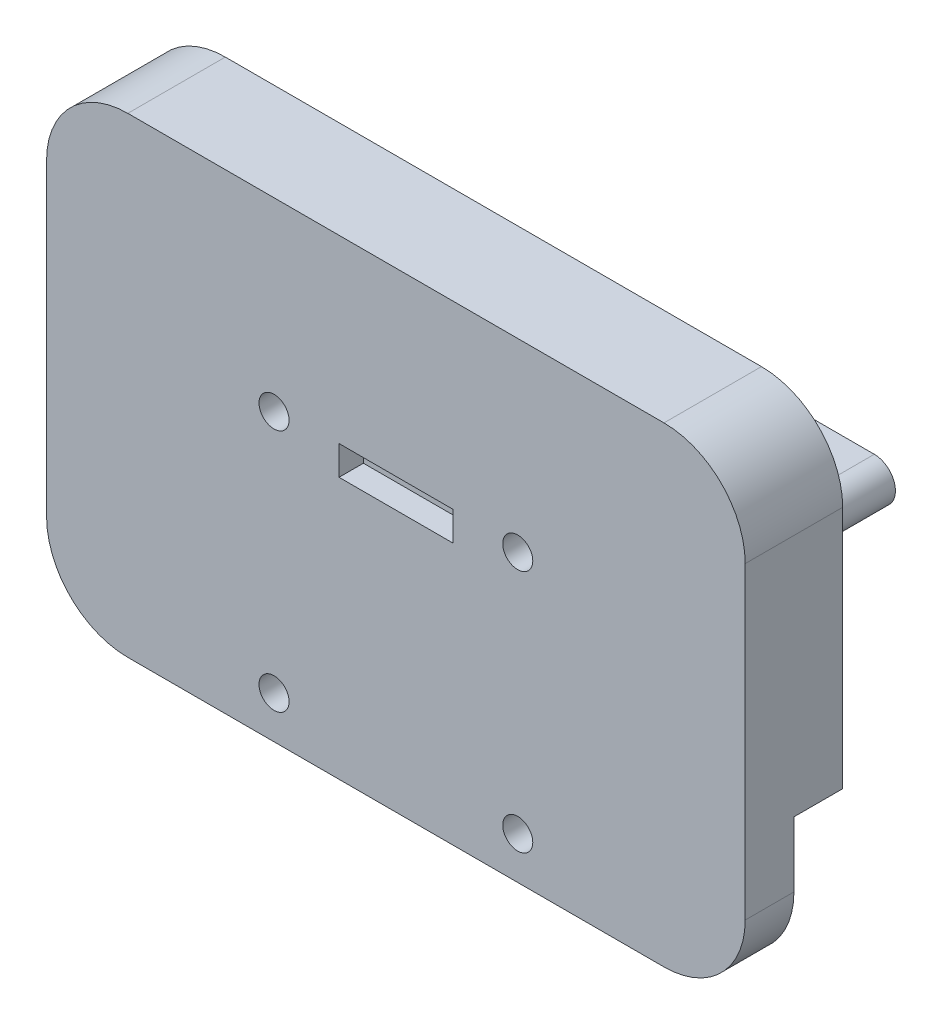
SolidWorks part; units mm, degrees
ref_plane "前视基准面" through (0, 0, 0) normal (0, 0, 1) x (1, 0, 0)
ref_plane "上视基准面" through (0, 0, 0) normal (0, 1, 0) x (1, 0, 0)
ref_plane "右视基准面" through (0, 0, 0) normal (1, 0, 0) x (0, 0, -1)
sketch "草图1" plane through (0, 0, 0) normal (0, 0, 1) x (1, 0, 0)
  line L1 (-13.5, 10) -> (13.5, 10)
  line L2 (-13.5, 10) -> (-13.5, -10)
  line L3 (-13.5, -10) -> (13.5, -10)
  line L4 (13.5, 10) -> (13.5, -10)
  line L5 (-13.5, 10) -> (13.5, -10) construction
  line L6 (-13.5, -10) -> (13.5, 10) construction
  point P0 (0, 0)
extrude "凸台-拉伸1" add sketch "草图1" along normal blind 4
ref_plane "基准面1" through (0, 0, 0) normal (-1, 0, 0) x (0, 0, 1)
extrude "切除-拉伸1" cut sketch "草图2" against normal blind 1.5
sketch "草图2" plane through (6.4149, -0.5973, 4) normal (0, 0, 1) x (1, 0, 0)
  line L8 (-9.8149, 8.3973) -> (-9.8149, 6.7973)
  line L9 (-3.0149, 8.3973) -> (-9.8149, 8.3973)
  line L10 (-3.0149, 6.7973) -> (-3.0149, 8.3973)
  line L11 (-9.8149, 6.7973) -> (-3.0149, 6.7973)
sketch "草图4" plane through (0, 0, 0) normal (0, 0, -1) x (-1, 0, 0)
  line L0 (-13.5, 10) -> (-13.5, 14)
  line L1 (-13.5, 14) -> (13.5, 14)
  line L2 (13.5, 14) -> (13.5, 10)
  line L4 (-13.5, 10) -> (-13.5, -10)
  line L5 (-13.5, -10) -> (13.5, -10)
  line L6 (13.5, -10) -> (13.5, 10)
  line L7 (13.5, 10) -> (-13.5, 10)
  line L8 (-13.5, 10) -> (-13.5, -6)
  line L10 (13.5, -6) -> (13.5, 10)
  line L12 (-13.5, -6) -> (13.5, -6)
  dimension "D1" = 0
extrude "凸台-拉伸2" add sketch "草图4" along normal blind 3
sketch "草图5" plane through (0, 10, 0) normal (0, 1, 0) x (1, 0, 0)
  line L4 (13.5, 0) -> (-13.5, 0)
  line L5 (-13.5, 0) -> (-13.5, -4)
  line L6 (-13.5, -4) -> (13.5, -4)
  line L7 (13.5, -4) -> (13.5, 0)
  line L8 (13.5, 0) -> (-13.5, 0)
  line L9 (-13.5, 0) -> (-13.5, -4)
  line L10 (-13.5, -4) -> (13.5, -4)
  line L11 (13.5, -4) -> (13.5, 0)
  dimension "D1" = 0
extrude "凸台-拉伸3" add sketch "草图5" along normal up to surface (4 mm away) up to face at (0, 14, -1.5)
sketch "草图9" plane through (0, 0, -3) normal (0, 0, -1) x (-1, 0, 0)
  line L4 (-13.5, 14) -> (-13.5, -6)
  line L5 (-13.5, -6) -> (13.5, -6)
  line L6 (13.5, -6) -> (13.5, 14)
  line L7 (13.5, 14) -> (-13.5, 14)
  line L8 (-13.5, 14) -> (-13.5, -6)
  line L9 (-13.5, -6) -> (13.5, -6)
  line L10 (13.5, -6) -> (13.5, 14)
  line L11 (13.5, 14) -> (-13.5, 14)
  dimension "D1" = 0
extrude "切除-拉伸4" cut sketch "草图9" against normal blind 2
sketch "草图10" plane through (-13.5, 0, 0) normal (-1, 0, 0) x (0, 0, 1)
  line L6 (-1, 14) -> (-1, -6)
  line L7 (-1, -6) -> (0, -6)
  line L8 (0, -6) -> (0, -10)
  line L9 (0, -10) -> (4, -10)
  line L10 (4, -10) -> (4, 14)
  line L11 (4, 14) -> (-1, 14)
  line L12 (-1, 14) -> (-1, -6)
  line L13 (-1, -6) -> (0, -6)
  line L14 (0, -6) -> (0, -10)
  line L15 (0, -10) -> (4, -10)
  line L16 (4, -10) -> (4, 14)
  line L17 (4, 14) -> (-1, 14)
  dimension "D1" = 0
extrude "凸台-拉伸6" add sketch "草图10" along normal blind 8
sketch "草图11" plane through (13.5, 0, 0) normal (1, 0, 0) x (0, 0, -1)
  line L6 (1, -6) -> (1, 14)
  line L7 (1, 14) -> (-4, 14)
  line L8 (-4, 14) -> (-4, -10)
  line L9 (-4, -10) -> (0, -10)
  line L10 (0, -10) -> (0, -6)
  line L11 (0, -6) -> (1, -6)
  line L12 (1, -6) -> (1, 14)
  line L13 (1, 14) -> (-4, 14)
  line L14 (-4, 14) -> (-4, -10)
  line L15 (-4, -10) -> (0, -10)
  line L16 (0, -10) -> (0, -6)
  line L17 (0, -6) -> (1, -6)
  dimension "D1" = 0
extrude "凸台-拉伸7" add sketch "草图11" along normal blind 8
sketch "草图12" plane through (0, 0, -1) normal (0, 0, -1) x (-1, 0, 0)
  line L1 (-21.5, -2) -> (21.5, -2)
  line L4 (21.5, 14) -> (-21.5, 14)
  line L5 (-21.5, 14) -> (-21.5, -6)
  line L6 (-21.5, -6) -> (21.5, -6)
  line L7 (21.5, -6) -> (21.5, 14)
  line L8 (21.5, 14) -> (-21.5, 14)
  line L9 (-21.5, 14) -> (-21.5, -2)
  line L11 (21.5, -2) -> (21.5, 14)
  dimension "D1" = 0
extrude "凸台-拉伸8" add sketch "草图12" along normal blind 20
extrude "切除-拉伸5" cut sketch "草图13" against normal blind 20
sketch "草图13" plane through (6.4149, -0.5973, -21) normal (0, 0, -1) x (-1, 0, 0)
  line L1 (26.2832, 7.1911) -> (21.0492, 4.7486)
  line L4 (27.9149, -1.4027) -> (27.9149, 14.5973)
  line L9 (18.9149, 6.1078) -> (18.9149, 8.0973)
  line L11 (19.9149, 9.0973) -> (25.8603, 9.0973)
  line L12 (-13.4534, 7.1911) -> (-8.2194, 4.7486)
  line L13 (-6.0851, 6.1078) -> (-6.0851, 8.0973)
  line L14 (-7.0851, 9.0973) -> (-13.0305, 9.0973)
  line L16 (27.9149, 14.5973) -> (-15.0851, 14.5973)
  line L18 (-15.0851, 14.5973) -> (-15.0851, -1.4027)
  line L20 (-15.0851, -1.4027) -> (27.9149, -1.4027)
  arc A1 (18.9149, 6.1078) -> (21.0492, 4.7486) centre (20.4149, 6.1078) ccw
  arc A3 (19.9149, 9.0973) -> (18.9149, 8.0973) centre (19.9149, 8.0973) ccw
  arc A5 (26.2832, 7.1911) -> (25.8603, 9.0973) centre (25.8603, 8.0973) ccw
  arc A12 (-8.2194, 4.7486) -> (-6.0851, 6.1078) centre (-7.5851, 6.1078) ccw
  arc A13 (-6.0851, 8.0973) -> (-7.0851, 9.0973) centre (-7.0851, 8.0973) ccw
  arc A14 (-13.0305, 9.0973) -> (-13.4534, 7.1911) centre (-13.0305, 8.0973) ccw
extrude "切除-拉伸6" cut sketch "草图14" against normal blind 16
sketch "草图14" plane through (6.4149, -0.5973, -21) normal (0, 0, -1) x (-1, 0, 0)
  line L6 (21.0492, 4.7486) -> (26.2832, 7.1911)
  line L7 (25.8603, 9.0973) -> (19.9149, 9.0973)
  line L8 (18.9149, 8.0973) -> (18.9149, 6.1078)
  line L12 (-7.0851, 9.0973) -> (-13.0305, 9.0973)
  line L13 (-13.4534, 7.1911) -> (-8.2194, 4.7486)
  line L14 (-6.0851, 6.1078) -> (-6.0851, 8.0973)
  arc A6 (26.2832, 7.1911) -> (25.8603, 9.0973) centre (25.8603, 8.0973) ccw
  arc A7 (19.9149, 9.0973) -> (18.9149, 8.0973) centre (19.9149, 8.0973) ccw
  arc A8 (18.9149, 6.1078) -> (21.0492, 4.7486) centre (20.4149, 6.1078) ccw
  arc A12 (-13.0305, 9.0973) -> (-13.4534, 7.1911) centre (-13.0305, 8.0973) ccw
  arc A13 (-8.2194, 4.7486) -> (-6.0851, 6.1078) centre (-7.5851, 6.1078) ccw
  arc A14 (-6.0851, 8.0973) -> (-7.0851, 9.0973) centre (-7.0851, 8.0973) ccw
sketch "草图15" plane through (0, 0, 4) normal (0, 0, 1) x (1, 0, 0)
  line L0 (-12.2968, 9.9409) -> (-18.5405, 6.1947)
  line L1 (-18.5405, 6.1947) -> (-18.9078, 5.4396)
  line L2 (-18.9078, 5.4396) -> (-12.2968, 9.4062)
  line L3 (-12.2968, 9.4062) -> (-12.2968, 9.9409)
  line L4 (-12.2968, 4.4409) -> (-18.5405, 0.6947)
  line L5 (-12.2968, 3.9062) -> (-12.2968, 4.4409)
  line L6 (-18.9078, -0.0604) -> (-12.2968, 3.9062)
  line L7 (-18.5405, 0.6947) -> (-18.9078, -0.0604)
  line L8 (-12.2968, -1.0591) -> (-18.5405, -4.8053)
  line L9 (-12.2968, -1.5938) -> (-12.2968, -1.0591)
  line L10 (-18.9078, -5.5604) -> (-12.2968, -1.5938)
  line L11 (-18.5405, -4.8053) -> (-18.9078, -5.5604)
  dimension "D1" = 3
sketch "草图17" plane through (0, 0, 4) normal (0, 0, 1) x (1, 0, 0)
  line L8 (3.5, 7.9) -> (-3.5, 7.9)
  line L9 (-3.5, 7.9) -> (-3.5, 6.1)
  line L10 (-3.5, 6.1) -> (3.5, 6.1)
  line L11 (3.5, 6.1) -> (3.5, 7.9)
extrude "切除-拉伸8" cut sketch "草图17" against normal blind 1.5
sketch "草图18" plane through (0, -10, 0) normal (0, -1, 0) x (1, 0, 0)
  line L4 (-21.5, 0) -> (21.5, 0)
  line L5 (21.5, 0) -> (21.5, 4)
  line L6 (21.5, 4) -> (-21.5, 4)
  line L7 (-21.5, 4) -> (-21.5, 0)
  line L8 (-21.5, 0) -> (21.5, 0)
  line L9 (21.5, 0) -> (21.5, 4)
  line L10 (21.5, 4) -> (-21.5, 4)
  line L11 (-21.5, 4) -> (-21.5, 0)
  dimension "D1" = 0
extrude "凸台-拉伸9" add sketch "草图18" along normal blind 5
sketch "草图19" plane through (0, 0, 4) normal (0, 0, 1) x (1, 0, 0)
  line L14 (3.5, 1.1) -> (3.5, 2.9)
  circle A8 centre (-7.5, -12.4) radius 0.925
  circle A9 centre (7.5, -12.4) radius 0.925
  circle A10 centre (-7.5, 2.6) radius 0.925
  circle A11 centre (7.5, 2.6) radius 0.925
extrude "切除-拉伸9" cut sketch "草图19" against normal blind 5 contours A10 | A11 | A9 | A8
sketch "草图20" plane through (0, 0, 4) normal (0, 0, 1) x (1, 0, 0)
  line L8 (-3.5, 2.9) -> (-3.5, 1.1)
  line L10 (-3.5, 2.9) -> (3.5, 2.9)
  line L11 (3.5, 2.9) -> (3.5, 1.1)
  line L12 (3.5, 1.1) -> (-3.5, 1.1)
extrude "切除-拉伸10" cut sketch "草图20" against normal blind 1.5
sketch "草图21" plane through (0, 0, 4) normal (0, 0, 1) x (1, 0, 0)
  line L0 (-3.5, 6.1) -> (3.5, 6.1) construction
  line L1 (-3.5, 6.1) -> (3.5, 6.1)
  line L2 (3.5, 7.9) -> (-3.5, 7.9) construction
  line L3 (3.5, 7.9) -> (-3.5, 7.9)
  line L4 (-3.5, 7.9) -> (-3.5, 6.1) construction
  line L5 (-3.5, 7.9) -> (-3.5, 6.1)
  line L6 (3.5, 6.1) -> (3.5, 7.9) construction
  line L7 (3.5, 6.1) -> (3.5, 7.9)
extrude "凸台-拉伸10" add sketch "草图21" against normal blind 1.5
fillet "圆角2" radius 5 4 edges at (21.5, -15, 2) (21.5, 14, 1.5) (-21.5, 14, 1.5) (-21.5, -15, 2)
sketch "草图22" plane through (0, 0, -5) normal (0, 0, -1) x (-1, 0, 0)
  line L0 (-13.5, 8.6) -> (-19.4454, 8.6)
  line L1 (-19.9106, 6.5032) -> (-14.6766, 4.0607)
  line L2 (-12.4, 5.5106) -> (-12.4, 7.5)
  line L3 (14.6343, 4.1513) -> (19.8683, 6.5938)
  line L4 (19.4454, 8.5) -> (13.5, 8.5)
  line L5 (12.5, 7.5) -> (12.5, 5.5106)
  line L6 (14.6343, 4.1513) -> (19.8683, 6.5938)
  line L7 (19.4454, 8.5) -> (13.5, 8.5)
  line L8 (12.5, 7.5) -> (12.5, 5.5106)
  line L9 (-13.5, 8.5) -> (-19.4454, 8.5)
  line L10 (-19.8683, 6.5938) -> (-14.6343, 4.1513)
  line L11 (-12.5, 5.5106) -> (-12.5, 7.5)
  line L12 (-13.5, 8.5) -> (-19.4454, 8.5)
  line L13 (-19.8683, 6.5938) -> (-14.6343, 4.1513)
  line L14 (-12.5, 5.5106) -> (-12.5, 7.5)
  line L15 (19.4454, 8.6) -> (13.5, 8.6)
  line L16 (12.4, 7.5) -> (12.4, 5.5106)
  line L17 (14.6766, 4.0607) -> (19.9106, 6.5032)
  arc A0 (-19.4454, 8.6) -> (-19.9106, 6.5032) centre (-19.4454, 7.5) ccw
  arc A1 (-14.6766, 4.0607) -> (-12.4, 5.5106) centre (-14, 5.5106) ccw
  arc A2 (-12.4, 7.5) -> (-13.5, 8.6) centre (-13.5, 7.5) ccw
  arc A3 (12.5, 5.5106) -> (14.6343, 4.1513) centre (14, 5.5106) ccw
  arc A4 (19.8683, 6.5938) -> (19.4454, 8.5) centre (19.4454, 7.5) ccw
  arc A5 (13.5, 8.5) -> (12.5, 7.5) centre (13.5, 7.5) ccw
  arc A6 (12.5, 5.5106) -> (14.6343, 4.1513) centre (14, 5.5106) ccw
  arc A7 (19.8683, 6.5938) -> (19.4454, 8.5) centre (19.4454, 7.5) ccw
  arc A8 (13.5, 8.5) -> (12.5, 7.5) centre (13.5, 7.5) ccw
  arc A9 (-12.5, 7.5) -> (-13.5, 8.5) centre (-13.5, 7.5) ccw
  arc A10 (-19.4454, 8.5) -> (-19.8683, 6.5938) centre (-19.4454, 7.5) ccw
  arc A11 (-14.6343, 4.1513) -> (-12.5, 5.5106) centre (-14, 5.5106) ccw
  arc A12 (-12.5, 7.5) -> (-13.5, 8.5) centre (-13.5, 7.5) ccw
  arc A13 (-19.4454, 8.5) -> (-19.8683, 6.5938) centre (-19.4454, 7.5) ccw
  arc A14 (-14.6343, 4.1513) -> (-12.5, 5.5106) centre (-14, 5.5106) ccw
  arc A15 (13.5, 8.6) -> (12.4, 7.5) centre (13.5, 7.5) ccw
  arc A16 (12.4, 5.5106) -> (14.6766, 4.0607) centre (14, 5.5106) ccw
  arc A17 (19.9106, 6.5032) -> (19.4454, 8.6) centre (19.4454, 7.5) ccw
  dimension "D1" = 0
  dimension "D2" = 0
  dimension "D3" = 0.1
extrude "凸台-拉伸11" add sketch "草图22" against normal up to surface (4 mm away) up to face at (8.425, 2.6, -1)
sketch "草图23" plane through (0, 0, -5) normal (0, 0, -1) x (-1, 0, 0)
  line L0 (-13.5, 8.8) -> (-19.4454, 8.8)
  line L1 (-19.9951, 6.322) -> (-14.7612, 3.8795)
  line L2 (-12.2, 5.5106) -> (-12.2, 7.5)
  line L3 (19.4454, 8.6) -> (13.5, 8.6)
  line L4 (12.4, 7.5) -> (12.4, 5.5106)
  line L5 (14.6766, 4.0607) -> (19.9106, 6.5032)
  line L6 (19.4454, 8.6) -> (13.5, 8.6)
  line L7 (12.4, 7.5) -> (12.4, 5.5106)
  line L8 (14.6766, 4.0607) -> (19.9106, 6.5032)
  line L9 (-13.5, 8.6) -> (-19.4454, 8.6)
  line L10 (-19.9106, 6.5032) -> (-14.6766, 4.0607)
  line L11 (-12.4, 5.5106) -> (-12.4, 7.5)
  line L12 (-13.5, 8.6) -> (-19.4454, 8.6)
  line L13 (-19.9106, 6.5032) -> (-14.6766, 4.0607)
  line L14 (-12.4, 5.5106) -> (-12.4, 7.5)
  line L15 (19.4454, 8.8) -> (13.5, 8.8)
  line L16 (12.2, 7.5) -> (12.2, 5.5106)
  line L17 (14.7612, 3.8795) -> (19.9951, 6.322)
  arc A0 (-19.4454, 8.8) -> (-19.9951, 6.322) centre (-19.4454, 7.5) ccw
  arc A1 (-14.7612, 3.8795) -> (-12.2, 5.5106) centre (-14, 5.5106) ccw
  arc A2 (-12.2, 7.5) -> (-13.5, 8.8) centre (-13.5, 7.5) ccw
  arc A3 (19.9106, 6.5032) -> (19.4454, 8.6) centre (19.4454, 7.5) ccw
  arc A4 (13.5, 8.6) -> (12.4, 7.5) centre (13.5, 7.5) ccw
  arc A5 (12.4, 5.5106) -> (14.6766, 4.0607) centre (14, 5.5106) ccw
  arc A6 (19.9106, 6.5032) -> (19.4454, 8.6) centre (19.4454, 7.5) ccw
  arc A7 (13.5, 8.6) -> (12.4, 7.5) centre (13.5, 7.5) ccw
  arc A8 (12.4, 5.5106) -> (14.6766, 4.0607) centre (14, 5.5106) ccw
  arc A9 (-12.4, 7.5) -> (-13.5, 8.6) centre (-13.5, 7.5) ccw
  arc A10 (-19.4454, 8.6) -> (-19.9106, 6.5032) centre (-19.4454, 7.5) ccw
  arc A11 (-14.6766, 4.0607) -> (-12.4, 5.5106) centre (-14, 5.5106) ccw
  arc A12 (-12.4, 7.5) -> (-13.5, 8.6) centre (-13.5, 7.5) ccw
  arc A13 (-19.4454, 8.6) -> (-19.9106, 6.5032) centre (-19.4454, 7.5) ccw
  arc A14 (-14.6766, 4.0607) -> (-12.4, 5.5106) centre (-14, 5.5106) ccw
  arc A15 (13.5, 8.8) -> (12.2, 7.5) centre (13.5, 7.5) ccw
  arc A16 (12.2, 5.5106) -> (14.7612, 3.8795) centre (14, 5.5106) ccw
  arc A17 (19.9951, 6.322) -> (19.4454, 8.8) centre (19.4454, 7.5) ccw
  dimension "D1" = 0
  dimension "D2" = 0
  dimension "D3" = 0.2
extrude "凸台-拉伸12" add sketch "草图23" against normal up to surface (4 mm away) up to face at (-15.4247, 6.7607, -1)
sketch "草图24" plane through (0, 0, 0) normal (0, 0, -1) x (-1, 0, 0)
  line L4 (-21.5, -6) -> (-21.5, -10)
  line L5 (-16.5, -15) -> (16.5, -15)
  line L6 (21.5, -10) -> (21.5, -6)
  line L7 (21.5, -6) -> (-21.5, -6)
  line L8 (-21.5, -6) -> (-21.5, -10)
  line L9 (-16.5, -15) -> (16.5, -15)
  line L10 (21.5, -10) -> (21.5, -6)
  line L11 (21.5, -6) -> (-21.5, -6)
  arc A2 (-21.5, -10) -> (-16.5, -15) centre (-16.5, -10) ccw
  arc A3 (16.5, -15) -> (21.5, -10) centre (16.5, -10) ccw
  arc A4 (-21.5, -10) -> (-16.5, -15) centre (-16.5, -10) ccw
  arc A5 (16.5, -15) -> (21.5, -10) centre (16.5, -10) ccw
  dimension "D1" = 0
extrude "切除-拉伸11" cut sketch "草图24" against normal blind 1
sketch "草图25" plane through (0, 0, -1) normal (0, 0, -1) x (-1, 0, 0)
  line L4 (16.5, 14) -> (-16.5, 14)
  line L5 (-21.5, 9) -> (-21.5, -6)
  line L6 (-21.5, -6) -> (21.5, -6)
  line L7 (21.5, -6) -> (21.5, 9)
  line L8 (16.5, 14) -> (-16.5, 14)
  line L9 (-21.5, 9) -> (-21.5, -6)
  line L10 (-21.5, -6) -> (21.5, -6)
  line L11 (21.5, -6) -> (21.5, 9)
  circle A0 centre (-7.5, 2.6) radius 0.925 construction
  circle A1 centre (-7.5, 2.6) radius 0.925
  arc A2 (-16.5, 14) -> (-21.5, 9) centre (-16.5, 9) ccw
  arc A3 (21.5, 9) -> (16.5, 14) centre (16.5, 9) ccw
  arc A4 (-16.5, 14) -> (-21.5, 9) centre (-16.5, 9) ccw
  arc A5 (21.5, 9) -> (16.5, 14) centre (16.5, 9) ccw
  circle A6 centre (7.5, 2.6) radius 0.925 construction
  circle A7 centre (7.5, 2.6) radius 0.925
  dimension "D1" = 0
extrude "凸台-拉伸13" add sketch "草图25" along normal blind 1
sketch "草图26" plane through (0, 0, -5) normal (0, 0, -1) x (-1, 0, 0)
  line L3 (-13.5, 8.8) -> (-19.4454, 8.8)
  line L4 (-19.9951, 6.322) -> (-14.7612, 3.8795)
  line L5 (-12.2, 5.5106) -> (-12.2, 7.5)
  line L6 (-13.5, 8.8) -> (-19.4454, 8.8)
  line L7 (-19.9951, 6.322) -> (-14.7612, 3.8795)
  line L8 (-12.2, 5.5106) -> (-12.2, 7.5)
  line L9 (19.4454, 8.8) -> (13.5, 8.8)
  line L10 (12.2, 7.5) -> (12.2, 5.5106)
  line L11 (14.7612, 3.8795) -> (19.9951, 6.322)
  line L12 (19.4454, 8.8) -> (13.5, 8.8)
  line L13 (12.2, 7.5) -> (12.2, 5.5106)
  line L14 (14.7612, 3.8795) -> (19.9951, 6.322)
  arc A3 (-12.2, 7.5) -> (-13.5, 8.8) centre (-13.5, 7.5) ccw
  arc A4 (-19.4454, 8.8) -> (-19.9951, 6.322) centre (-19.4454, 7.5) ccw
  arc A5 (-14.7612, 3.8795) -> (-12.2, 5.5106) centre (-14, 5.5106) ccw
  arc A6 (-12.2, 7.5) -> (-13.5, 8.8) centre (-13.5, 7.5) ccw
  arc A7 (-19.4454, 8.8) -> (-19.9951, 6.322) centre (-19.4454, 7.5) ccw
  arc A8 (-14.7612, 3.8795) -> (-12.2, 5.5106) centre (-14, 5.5106) ccw
  arc A9 (19.9951, 6.322) -> (19.4454, 8.8) centre (19.4454, 7.5) ccw
  arc A10 (13.5, 8.8) -> (12.2, 7.5) centre (13.5, 7.5) ccw
  arc A11 (12.2, 5.5106) -> (14.7612, 3.8795) centre (14, 5.5106) ccw
  arc A12 (19.9951, 6.322) -> (19.4454, 8.8) centre (19.4454, 7.5) ccw
  arc A13 (13.5, 8.8) -> (12.2, 7.5) centre (13.5, 7.5) ccw
  arc A14 (12.2, 5.5106) -> (14.7612, 3.8795) centre (14, 5.5106) ccw
  dimension "D1" = 0
  dimension "D2" = 0
extrude "凸台-拉伸14" add sketch "草图26" along normal blind 1
